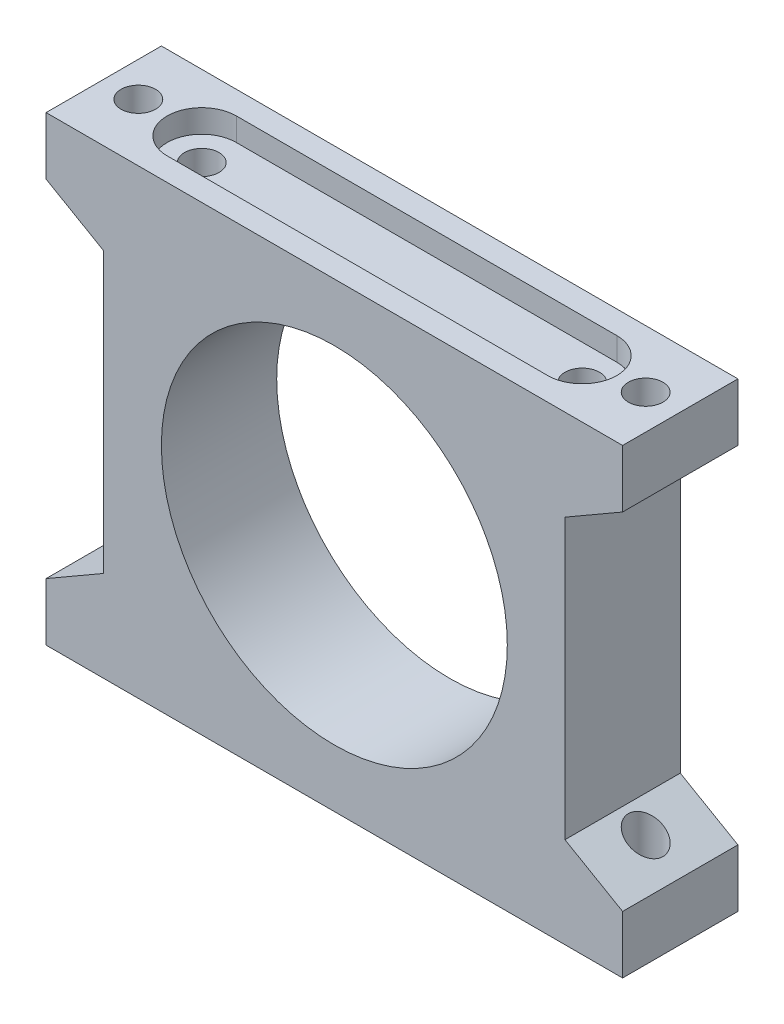
SolidWorks part; units mm, degrees
material "6061 合金"
ref_plane "前视基准面" through (0, 0, 0) normal (0, 0, 1) x (1, 0, 0)
ref_plane "上视基准面" through (0, 0, 0) normal (0, 1, 0) x (1, 0, 0)
ref_plane "右视基准面" through (0, 0, 0) normal (1, 0, 0) x (0, 0, -1)
sketch "草图1" plane through (0, 0, 0) normal (0, 0, 1) x (1, 0, 0)
  line L0 (0, 0) -> (0, 51.3639) construction
  line L1 (0, 0) -> (-52.3659, 0) construction
  line L3 (-25, -20) -> (-25, -15)
  line L4 (-25, 20) -> (25, 20)
  line L5 (25, 20) -> (25, 15)
  line L7 (-25, -20) -> (25, -20)
  line L8 (-25, 15) -> (-20, 12.1132)
  line L9 (-20, 12.1132) -> (-20, -12.1132)
  line L10 (-20, -12.1132) -> (-25, -15)
  line L12 (20, -12.1132) -> (25, -15)
  line L13 (20, 12.1132) -> (20, -12.1132)
  line L14 (25, 15) -> (20, 12.1132)
  line L15 (-25, 15) -> (-25, 20)
  line L16 (25, -15) -> (25, -20)
  circle A0 centre (0, 0) radius 15 construction
  circle A2 centre (0, 0) radius 15
  dimension "D1" = 30
  dimension "D2" = 50
  dimension "D3" = 40
  dimension "D4" = 120
  dimension "D5" = 5
  dimension "D6" = 5
extrude "凸台-拉伸1" add sketch "草图1" along normal blind 10
sketch "草图2" plane through (0, 20, 0) normal (0, 1, 0) x (1, 0, 0)
  line L0 (-25, -5) -> (31.7775, -5) construction
  line L1 (-25, -10) -> (-25, 0) construction
  line L2 (0, 0) -> (0, -20.4118) construction
  line L3 (25, 0) -> (-25, 0) construction
  circle A0 centre (-22, -5) radius 1.5
  circle A1 centre (22, -5) radius 1.5
  dimension "D1" = 3
  dimension "D2" = 44
extrude "切除-拉伸1" cut sketch "草图2" against normal through all and the other way through all
sketch "草图3" plane through (0, 20, 0) normal (0, 1, 0) x (1, 0, 0)
  line L0 (-25, -5) -> (25, -5) construction
  line L1 (-25, -10) -> (-25, 0) construction
  line L2 (25, -10) -> (25, 0) construction
  line L3 (-16.5, -5) -> (16.5, -5) construction
  line L4 (-16.5, -2) -> (16.5, -2)
  line L5 (-16.5, -8) -> (16.5, -8)
  line L6 (25, 0) -> (-25, 0) construction
  arc A0 (-16.5, -2) -> (-16.5, -8) centre (-16.5, -5) ccw
  arc A1 (16.5, -8) -> (16.5, -2) centre (16.5, -5) ccw
  point P8 (0, -5)
  point P13 (0, -5)
  dimension "D1" = 33
  dimension "D2" = 2
extrude "切除-拉伸2" cut sketch "草图3" against normal blind 2
sketch "草图4" plane through (0, 18, 0) normal (0, 1, 0) x (1, 0, 0)
  line L0 (0, 0) -> (0, -10) construction
  line L1 (25, -10) -> (-25, -10) construction
  circle A0 centre (-16.5, -5) radius 1.5
  arc A1 (-16.5, -2) -> (-16.5, -8) centre (-16.5, -5) ccw construction
  circle A2 centre (16.5, -5) radius 1.5
  dimension "D1" = 3
extrude "切除-拉伸3" cut sketch "草图4" against normal blind 3
mirror "镜向1" about plane through (0, 0, 0) normal (0, 1, 0) of "切除-拉伸2", "切除-拉伸3"
